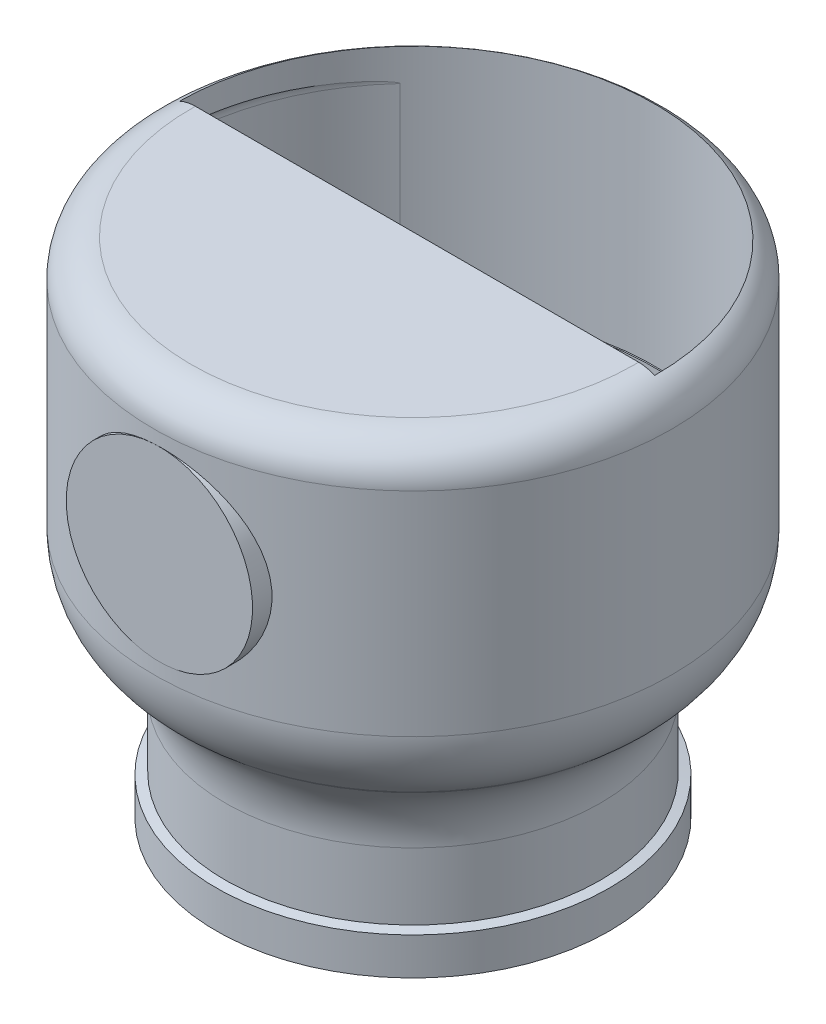
SolidWorks part; units mm, degrees
ref_plane "Front Plane" through (0, 0, 0) normal (0, 0, 1) x (1, 0, 0)
ref_plane "Top Plane" through (0, 0, 0) normal (0, 1, 0) x (1, 0, 0)
ref_plane "Right Plane" through (0, 0, 0) normal (1, 0, 0) x (0, 0, -1)
sketch "Sketch1" plane through (0, 0, 0) normal (0, 0, 1) x (1, 0, 0)
  line L0 (2.7649, 7.8218) -> (2.7649, 58.3592) construction
  line L1 (20.9, 0) -> (23.8716, 0)
  line L2 (23.8716, 0) -> (23.8716, 4)
  line L3 (23.8716, 4) -> (22.9, 4.2367)
  line L4 (22.9, 4.2367) -> (22.9, 11.4043)
  line L6 (20.9, 0) -> (20.9, 14)
  line L8 (2.7649, 52) -> (2.7649, 54)
  line L10 (17.2603, 17) -> (2.7649, 17)
  line L12 (19.9, 15) -> (2.7649, 15)
  line L13 (2.7649, 17) -> (2.7649, 15)
  line L15 (23.6882, 19.3396) -> (24.9883, 20.4305)
  line L16 (28.5604, 28.091) -> (28.5604, 50)
  line L17 (26.4721, 19.0648) -> (26.9883, 19.4979)
  line L18 (30.5604, 27.1583) -> (30.5604, 50)
  line L19 (26.5604, 52) -> (2.7649, 52)
  line L20 (26.5604, 54) -> (2.7649, 54)
  arc A0 (28.5604, 50) -> (26.5604, 52) centre (26.5604, 50) ccw
  arc A1 (30.5604, 50) -> (26.5604, 54) centre (26.5604, 50) ccw
  arc A2 (26.4721, 19.0648) -> (22.9, 11.4043) centre (32.9, 11.4043) ccw
  arc A3 (26.9883, 19.4979) -> (30.5604, 27.1583) centre (20.5604, 27.1583) ccw
  arc A4 (24.9883, 20.4305) -> (28.5604, 28.091) centre (18.5604, 28.091) ccw
  arc A5 (17.2603, 17) -> (23.6882, 19.3396) centre (17.2603, 27) ccw
  arc A6 (20.9, 14) -> (19.9, 15) centre (19.9, 14) ccw
  point P11 (22.9, 54)
  point P28 (28.5604, 23.4279)
  point P31 (20.9, 17)
  dimension "D8" = 2
  dimension "D9" = 4
  dimension "D4" = 2
  dimension "D16" = 10
  dimension "D17" = 10
  dimension "D18" = 10
  dimension "D19" = 1
  dimension "D1" = 2
  dimension "D2" = 4
  dimension "D3" = 1
  dimension "D5" = 140
  dimension "D6" = 2
  dimension "D7" = 2.9716
  dimension "D10" = 2
  dimension "D11" = 15
  dimension "D12" = 35
  dimension "D13" = 37
  dimension "D14" = 2
  dimension "D15" = 10
revolve "Revolve1" add sketch "Sketch1" angle 360 about L0
ref_plane "Plane1" through (0, 4, 0) normal (0, 1, 0) x (1, 0, 0)
sketch "Sketch3" plane through (0, 0, 0) normal (0, 0, 1) x (1, 0, 0)
  point P0 (1.2404, 19.1989)
ref_point "Point1"
ref_plane "Plane2" through (0, 0, 22.9) normal (0, 0, 1) x (1, 0, 0)
ref_plane "Plane3" through (0, 0, 27.7955) normal (0, 0, 1) x (1, 0, 0)
ref_plane "Plane4" through (0, 54, 0) normal (0, 1, 0) x (1, 0, 0)
sketch "Sketch9" plane through (0, 54, 0) normal (0, 1, 0) x (1, 0, 0)
  line L0 (-22.7351, 0.4376) -> (28.2649, 0.4376)
  arc A0 (28.2649, 0.4376) -> (-22.7351, 0.4376) centre (2.7649, 0.4376) ccw
  circle A3 centre (2.7649, 0) radius 23.7955 construction
  point P1 (0, 0)
  dimension "D1" = 51
  dimension "D3" = 25.5
  dimension "D2" = 25.5
extrude "Cut-Extrude2" cut sketch "Sketch9" against normal blind 25
sketch "Sketch10" plane through (0, 0, 27.7955) normal (0, 0, 1) x (1, 0, 0)
  line L0 (30.5604, 27.1583) -> (-25.0306, 27.1583) construction
  circle A0 centre (3.3463, 38.6583) radius 10
  dimension "D1" = 20
  dimension "D2" = 11.5
extrude "Boss-Extrude1" add sketch "Sketch10" against normal blind 5
